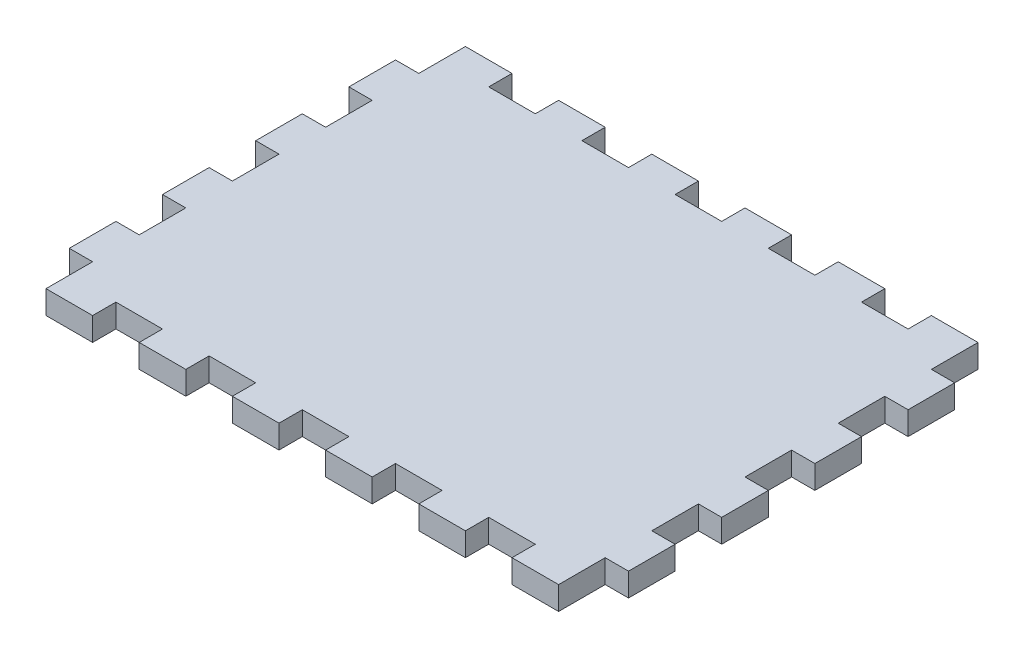
SolidWorks part; units mm, degrees
ref_plane "Front Plane" through (0, 0, 0) normal (0, 0, 1) x (1, 0, 0)
ref_plane "Top Plane" through (0, 0, 0) normal (0, 1, 0) x (1, 0, 0)
ref_plane "Right Plane" through (0, 0, 0) normal (1, 0, 0) x (0, 0, -1)
sketch "Sketch1" plane through (0, 0, 0) normal (0, 1, 0) x (1, 0, 0)
  line L0 (55, 45) -> (45, 45)
  line L5 (45, 45) -> (45, 40)
  line L6 (45, 40) -> (35, 40)
  line L7 (35, 40) -> (35, 45)
  line L8 (35, 45) -> (25, 45)
  line L9 (25, 45) -> (25, 40)
  line L10 (25, 40) -> (15, 40)
  line L11 (15, 40) -> (15, 45)
  line L12 (15, 45) -> (5, 45)
  line L13 (5, 45) -> (5, 40)
  line L14 (5, 40) -> (-5, 40)
  line L15 (-5, 40) -> (-5, 45)
  line L16 (-5, 45) -> (-15, 45)
  line L17 (-15, 45) -> (-15, 40)
  line L18 (-15, 40) -> (-25, 40)
  line L19 (-25, 40) -> (-25, 45)
  line L20 (-25, 45) -> (-35, 45)
  line L21 (-35, 45) -> (-35, 40)
  line L22 (-35, 40) -> (-45, 40)
  line L23 (-45, 40) -> (-45, 45)
  line L24 (-45, 45) -> (-55, 45)
  line L25 (-55, 45) -> (-55, 40)
  line L26 (-55, 40) -> (-55, 35)
  line L27 (-55, 35) -> (-60, 35)
  line L28 (-60, 35) -> (-60, 25)
  line L29 (-60, 25) -> (-55, 25)
  line L30 (-55, 25) -> (-55, 15)
  line L31 (-55, 15) -> (-60, 15)
  line L32 (-60, 15) -> (-60, 5)
  line L33 (-60, 5) -> (-55, 5)
  line L34 (-55, 5) -> (-55, -5)
  line L35 (-55, -5) -> (-60, -5)
  line L36 (-60, -5) -> (-60, -15)
  line L37 (-60, -15) -> (-55, -15)
  line L38 (-55, -15) -> (-55, -25)
  line L39 (-55, -25) -> (-60, -25)
  line L40 (-60, -25) -> (-60, -35)
  line L41 (-60, -35) -> (-55, -35)
  line L42 (-55, -35) -> (-55, -40)
  line L43 (-55, -40) -> (-55, -45)
  line L44 (-55, -45) -> (-45, -45)
  line L45 (-45, -45) -> (-45, -40)
  line L46 (-45, -40) -> (-35, -40)
  line L47 (-35, -40) -> (-35, -45)
  line L48 (-35, -45) -> (-25, -45)
  line L49 (-25, -45) -> (-25, -40)
  line L50 (-25, -40) -> (-15, -40)
  line L51 (-15, -40) -> (-15, -45)
  line L52 (-15, -45) -> (-5, -45)
  line L53 (-5, -45) -> (-5, -40)
  line L54 (-5, -40) -> (5, -40)
  line L55 (5, -40) -> (5, -45)
  line L56 (5, -45) -> (15, -45)
  line L57 (15, -45) -> (15, -40)
  line L58 (15, -40) -> (25, -40)
  line L59 (25, -40) -> (25, -45)
  line L60 (25, -45) -> (35, -45)
  line L61 (35, -45) -> (35, -40)
  line L62 (35, -40) -> (45, -40)
  line L63 (45, -40) -> (45, -45)
  line L64 (45, -45) -> (55, -45)
  line L65 (55, -45) -> (55, -40)
  line L66 (55, -40) -> (55, -35)
  line L67 (55, -35) -> (60, -35)
  line L68 (60, -35) -> (60, -25)
  line L69 (60, -25) -> (55, -25)
  line L70 (55, -25) -> (55, -15)
  line L71 (55, -15) -> (60, -15)
  line L72 (60, -15) -> (60, -5)
  line L73 (60, -5) -> (55, -5)
  line L74 (55, -5) -> (55, 5)
  line L75 (55, 5) -> (60, 5)
  line L76 (60, 5) -> (60, 15)
  line L77 (60, 15) -> (55, 15)
  line L78 (55, 15) -> (55, 25)
  line L79 (55, 25) -> (60, 25)
  line L80 (60, 25) -> (60, 35)
  line L81 (60, 35) -> (55, 35)
  line L82 (55, 35) -> (55, 40)
  line L83 (55, 40) -> (55, 45)
  line L88 (-60, 45) -> (60, -45) construction
  point P87 (0, 0)
  dimension "D1" = 0
extrude "Boss-Extrude1" add sketch "Sketch1" along normal mid plane 5
sketch "Sketch2" plane through (0, 2.5, 0) normal (0, 1, 0) x (1, 0, 0)
  text T0 "Top/Bottom"
extrude "Cut-Extrude1" [suppressed] cut sketch "Sketch2" against normal blind 3
